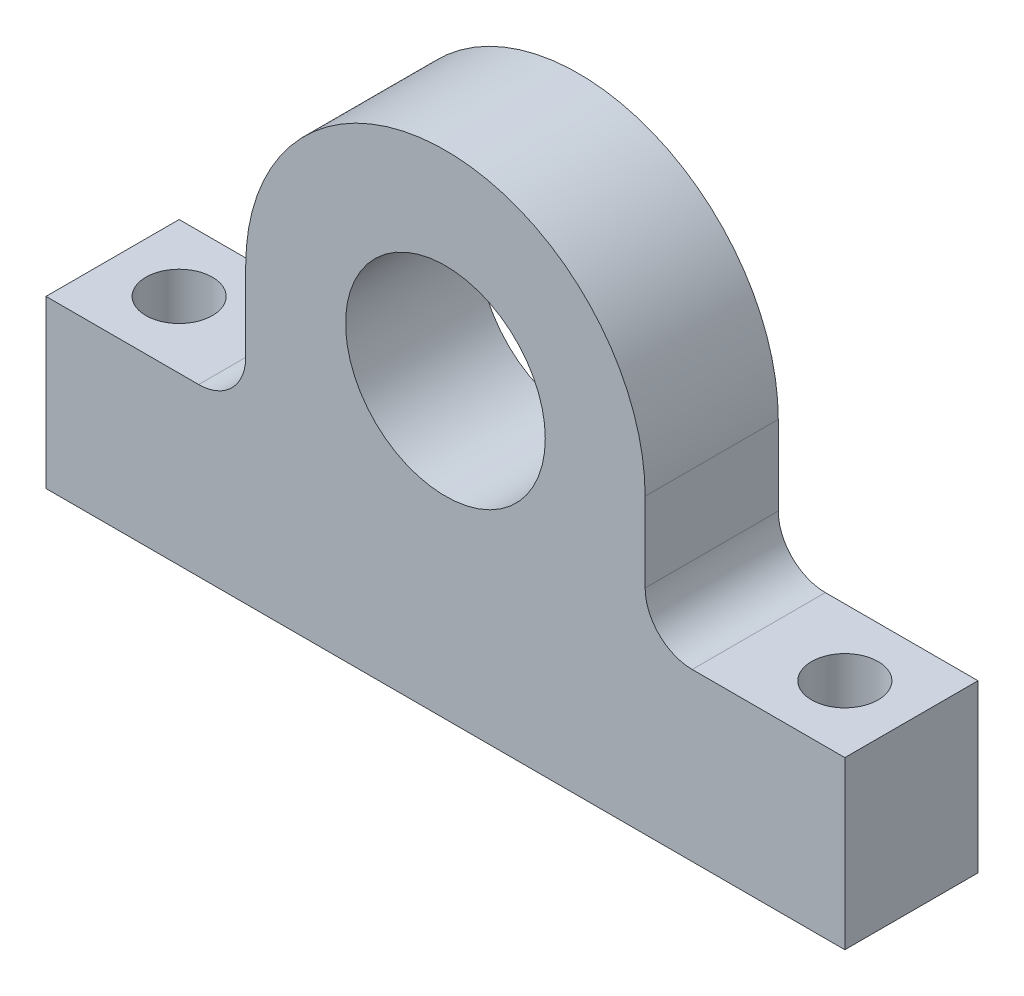
SolidWorks part; units mm, degrees
ref_plane "Front Plane" through (0, 0, 0) normal (0, 0, 1) x (1, 0, 0)
ref_plane "Top Plane" through (0, 0, 0) normal (0, 1, 0) x (1, 0, 0)
ref_plane "Right Plane" through (0, 0, 0) normal (1, 0, 0) x (0, 0, -1)
sketch "Sketch1" plane through (0, 0, 0) normal (0, 0, 1) x (1, 0, 0)
  line L0 (-15, -1.4645) -> (-15, 4.5)
  line L1 (0, -10) -> (-20, -10)
  line L2 (0, -10) -> (20, -10)
  line L4 (-20, -10) -> (-30, -10)
  line L5 (15, -1.4645) -> (15, 4.5)
  line L7 (20, -10) -> (30, -10)
  line L8 (30, -10) -> (30, -5)
  line L9 (30, -5) -> (18.5355, -5)
  line L10 (-30, -10) -> (-30, -5)
  line L11 (-30, -5) -> (-18.5355, -5)
  circle A0 centre (0, 4.5) radius 7.5
  arc A3 (15, -1.4645) -> (18.5355, -5) centre (18.5355, -1.4645) ccw
  arc A4 (-15, -1.4645) -> (-18.5355, -5) centre (-18.5355, -1.4645) cw
  arc A5 (15, 4.5) -> (-15, 4.5) centre (0, 4.5) ccw
  point P0 (0, 0)
  dimension "D2" = 5
extrude "Boss-Extrude2" add sketch "Sketch1" along normal blind 10
sketch "Sketch2" plane through (0, -5, 0) normal (0, 1, 0) x (1, 0, 0)
  line L0 (-30, 0) -> (-25, 0) construction
  line L1 (-18.5355, 0) -> (-30, 0) construction
  line L2 (0, 0) -> (0, 7.5358) construction
  circle A0 centre (-25, -5) radius 2.5
  circle A1 centre (25, -5) radius 2.5
extrude "Cut-Extrude1" cut sketch "Sketch2" against normal blind 10
sketch "Sketch3" plane through (0, -10, 0) normal (0, -1, 0) x (1, 0, 0)
  line L1 (-30, 10) -> (30, 10)
  line L2 (-30, 10) -> (-30, 0)
  line L3 (-30, 0) -> (30, 0)
  line L4 (30, 10) -> (30, 0)
  circle A0 centre (-25, 5) radius 2.5
  circle A1 centre (25, 5) radius 2.5
extrude "Boss-Extrude3" add sketch "Sketch3" along normal blind 7.5
